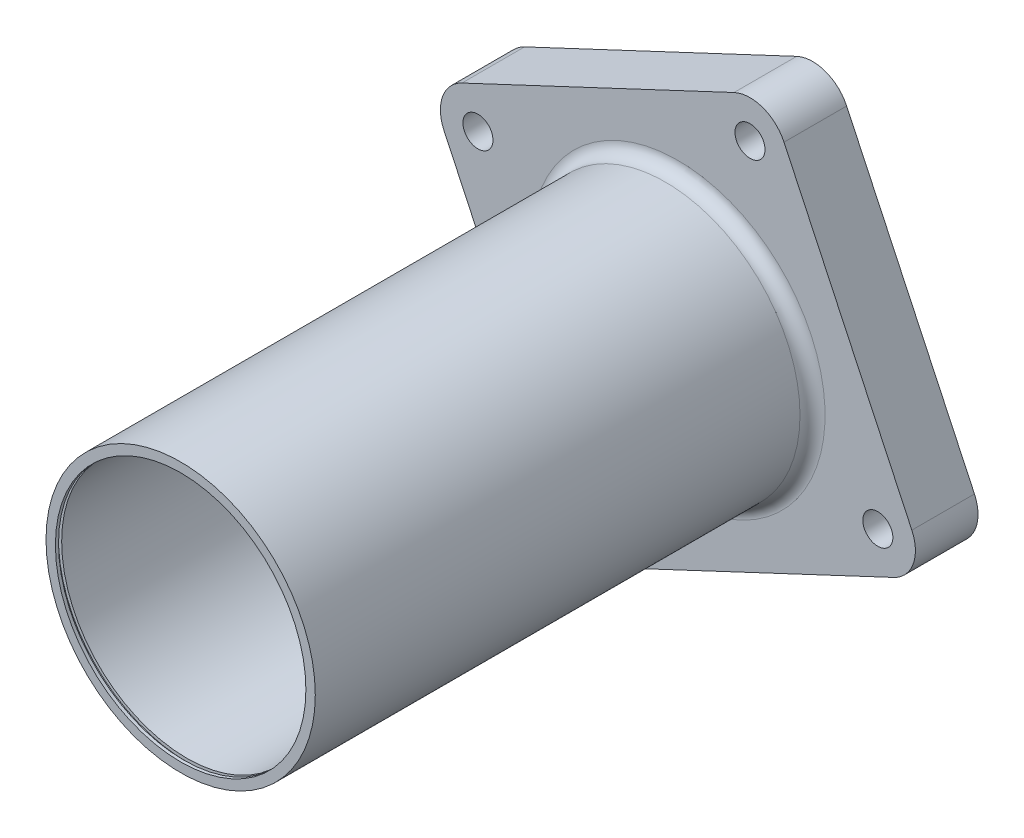
SolidWorks part; units mm, degrees
ref_plane "Front Plane" through (0, 0, 0) normal (0, 0, 1) x (1, 0, 0)
ref_plane "Top Plane" through (0, 0, 0) normal (0, 1, 0) x (1, 0, 0)
ref_plane "Right Plane" through (0, 0, 0) normal (1, 0, 0) x (0, 0, -1)
sketch "Sketch1" plane through (0, 0, 0) normal (0, 0, 1) x (1, 0, 0)
  circle A0 centre (0, 0) radius 107.5
  circle A1 centre (0, 0) radius 100
  dimension "D1" = 215
  dimension "D2" = 7.5
extrude "Boss-Extrude1" add sketch "Sketch1" along normal blind 187
sketch "Sketch2" plane through (0, 0, 0) normal (0, 0, -1) x (-1, 0, 0)
  line L5 (-199.5471, -71.979) -> (-71.979, 199.5471)
  line L6 (-71.979, 199.5471) -> (63.784, 135.763)
  line L7 (0, 0) -> (63.784, 135.763) construction
  line L8 (71.979, -199.5471) -> (199.5471, 71.979)
  line L9 (63.784, 135.763) -> (199.5471, 71.979)
  line L10 (-63.784, -135.763) -> (71.979, -199.5471)
  line L11 (-199.5471, -71.979) -> (-63.784, -135.763)
  point P0 (0, 0)
  point P11 (135.763, -63.784)
  dimension "D2" = 150
extrude "Boss-Extrude2" add sketch "Sketch2" along normal blind 30
sketch "Sketch3" plane through (0, 0, -30) normal (0, 0, -1) x (-1, 0, 0)
  line L4 (-199.5471, -71.979) -> (71.979, -199.5471)
  line L5 (71.979, -199.5471) -> (199.5471, 71.979)
  line L6 (199.5471, 71.979) -> (-71.979, 199.5471)
  line L7 (-71.979, 199.5471) -> (-199.5471, -71.979)
  line L8 (-199.5471, -71.979) -> (71.979, -199.5471)
  line L9 (71.979, -199.5471) -> (199.5471, 71.979)
  line L10 (199.5471, 71.979) -> (-71.979, 199.5471)
  line L11 (-71.979, 199.5471) -> (-199.5471, -71.979)
  dimension "D1" = 0
extrude "Boss-Extrude3" add sketch "Sketch3" along normal blind 20
fillet "Fillet1" radius 30 4 edges at (199.5471, -71.979, -25) (-71.979, -199.5471, -25) (-199.5471, 71.979, -25) (71.979, 199.5471, -25)
fillet "Fillet2" radius 10 1 edges at (107.5, 0, 0)
sketch "Sketch5" plane through (0, 0, -50) normal (0, 0, -1) x (-1, 0, 0)
  circle A0 centre (0, 0) radius 105
  dimension "D1" = 210
extrude "Cut-Extrude1" cut sketch "Sketch5" against normal blind 942
sketch "Sketch6" plane through (0, 0, 187) normal (0, 0, 1) x (1, 0, 0)
  circle A0 centre (0, 0) radius 107.5
  dimension "D1" = 215
extrude "Boss-Extrude6" add sketch "Sketch6" along normal blind 10
sketch "Sketch7" plane through (0, 0, 197) normal (0, 0, 1) x (1, 0, 0)
  circle A0 centre (0, 0) radius 107.5
  circle A1 centre (0, 0) radius 100
  dimension "D1" = 215
  dimension "D2" = 7.5
extrude "Boss-Extrude7" add sketch "Sketch7" along normal blind 200
sketch "Sketch8" plane through (0, 0, 197) normal (0, 0, 1) x (1, 0, 0)
  circle A0 centre (0, 0) radius 95
  circle A1 centre (0, 0) radius 102.5
  dimension "D1" = 190
  dimension "D2" = 205
extrude "Boss-Extrude8" add sketch "Sketch8" along normal blind 4
sketch "Sketch9" plane through (0, 0, 397) normal (0, 0, 1) x (1, 0, 0)
  circle A0 centre (0, 0) radius 102.5
  dimension "D1" = 205
extrude "Cut-Extrude2" cut sketch "Sketch9" against normal blind 2.5 from offset 2.5 offset against normal yes
sketch "Sketch10" plane through (0, 0, 187) normal (0, 0, -1) x (-1, 0, 0)
  circle A0 centre (0, 0) radius 31
  dimension "D1" = 62
extrude "Cut-Extrude3" cut sketch "Sketch10" against normal blind 28
hole_wizard "CBORE for M4 Hex Head Cap Screw1" positions "Sketch11" profile "Sketch13" counterbore size "M4" standard "ISO"
sketch "Sketch11" plane through (0, 0, 197) normal (0, 0, 1) x (1, 0, 0)
  circle A0 centre (0, 0) radius 70 construction
  point P36 (63.3561, 29.7659)
  point P46 (65.8472, -23.7518)
  point P47 (29.7659, -63.3561)
  point P48 (-23.7518, -65.8472)
  point P49 (-63.3561, -29.7659)
  point P50 (-65.8472, 23.7518)
  point P51 (-29.7659, 63.3561)
  point P52 (23.7518, 65.8472)
  dimension "D1" = 140
  dimension "D2" = 8
sketch "Sketch13" plane through (23.7518, 65.8472, 197) normal (1, 0, 0) x (0, -1, 0)
  line L0 (0, 0) -> (0, 11.3519)
  line L1 (0, 11.3519) -> (2.25, 10)
  line L2 (2.25, 10) -> (2.25, 2.8)
  line L3 (2.25, 2.8) -> (5.5415, 2.8)
  line L5 (5.5415, 2.8) -> (5.5415, 0.025)
  line L6 (5.5415, 0.025) -> (5.5665, 0)
  line L7 (5.5665, 0) -> (0, 0)
  line L8 (-5.5415, 0.025) -> (-5.5665, 0) construction
  line L10 (0, 11.3519) -> (-2.25, 10) construction
  line L11 (0, -6.35) -> (0, 107.95) construction
  dimension "Hole Dia." = 4.5
  dimension "Hole Depth" = 10
  dimension "C'Bore Dia." = 11.083
  dimension "C'Bore Depth" = 2.8
  dimension "Near C'Sink Dia." = 11.133
  dimension "Near C'Sink Angle" = 90
  dimension "Drill Angle" = 118
hole_wizard "CBORE for M3 Hex Head Cap Screw1" positions "Sketch18" profile "Sketch19" counterbore size "M3" standard "ISO"
sketch "Sketch18" plane through (0, 0, 197) normal (0, 0, 1) x (1, 0, 0)
  circle A0 centre (0, 0) radius 42 construction
  point P33 (38.0136, 17.8595)
  point P39 (39.5083, -14.2511)
  point P40 (17.8595, -38.0136)
  point P41 (-14.2511, -39.5083)
  point P42 (-38.0136, -17.8595)
  point P43 (-39.5083, 14.2511)
  point P44 (-17.8595, 38.0136)
  point P45 (14.2511, 39.5083)
  dimension "D1" = 84
  dimension "D2" = 8
sketch "Sketch19" plane through (14.2511, 39.5083, 197) normal (1, 0, 0) x (0, -1, 0)
  line L0 (0, 0) -> (0, 11.0215)
  line L1 (0, 11.0215) -> (1.7, 10)
  line L2 (1.7, 10) -> (1.7, 2)
  line L3 (1.7, 2) -> (4.6755, 2)
  line L5 (4.6755, 2) -> (4.6755, 0.025)
  line L6 (4.6755, 0.025) -> (4.7005, 0)
  line L7 (4.7005, 0) -> (0, 0)
  line L8 (-4.6755, 0.025) -> (-4.7005, 0) construction
  line L10 (0, 11.0215) -> (-1.7, 10) construction
  line L11 (0, -6.35) -> (0, 107.95) construction
  dimension "Hole Dia." = 3.4
  dimension "Hole Depth" = 10
  dimension "C'Bore Dia." = 9.351
  dimension "C'Bore Depth" = 2
  dimension "Near C'Sink Dia." = 9.401
  dimension "Near C'Sink Angle" = 90
  dimension "Drill Angle" = 118
sketch "Sketch20" plane through (0, 0, 187) normal (0, 0, -1) x (-1, 0, 0)
  circle A0 centre (0, 0) radius 105
  circle A1 centre (0, 0) radius 90
  dimension "D1" = 210
  dimension "D2" = 180
extrude "Boss-Extrude9" add sketch "Sketch20" along normal up to surface (237 mm away) up to face at (-105, 0, -50)
sketch "Sketch21" plane through (0, 0, 0) normal (0, 0, 1) x (1, 0, 0)
  line L0 (-63.784, 135.763) -> (-86.6579, 184.4495) construction
  line L1 (-172.3945, 84.7358) -> (44.8264, 186.7902) construction
  circle A0 centre (-159.6376, 57.5832) radius 12
  circle A1 centre (57.5832, 159.6376) radius 12
  circle A2 centre (159.6376, -57.5832) radius 12
  circle A3 centre (-57.5832, -159.6376) radius 12
  point P22 (0, 0)
  point P26 (0, 0)
  dimension "D1" = 24
  dimension "D2" = 24
  dimension "D3" = 24
  dimension "D4" = 24
extrude "Cut-Extrude4" cut sketch "Sketch21" against normal blind 421
